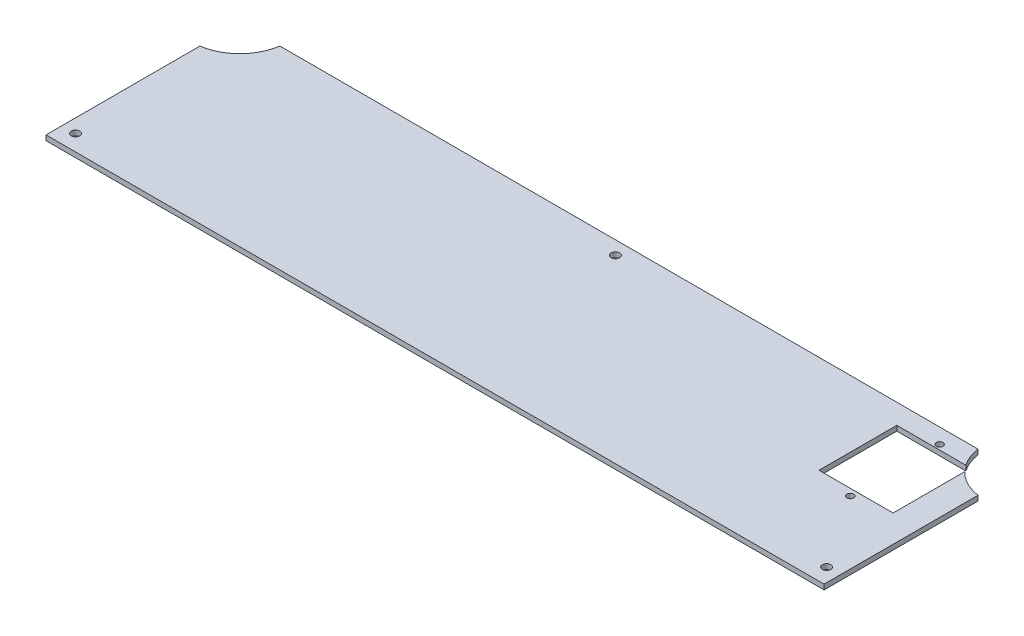
SolidWorks part; units mm, degrees
ref_plane "Alzado" through (0, 0, 0) normal (0, 0, 1) x (1, 0, 0)
ref_plane "Planta" through (0, 0, 0) normal (0, 1, 0) x (1, 0, 0)
ref_plane "Vista lateral" through (0, 0, 0) normal (1, 0, 0) x (0, 0, -1)
sketch "Croquis1" plane through (0, 0, 0) normal (0, 1, 0) x (1, 0, 0)
  line L0 (-230.75, -57.5) -> (230.75, -57.5)
  line L1 (-230.75, 33.7872) -> (-230.75, -57.5)
  line L2 (207.0372, 57.5) -> (-207.0372, 57.5)
  line L3 (170.75, 45.6295) -> (211.6821, 45.6295)
  line L4 (170.75, -0.5) -> (170.75, 45.6295)
  line L5 (214.6745, -0.5) -> (170.75, -0.5)
  line L6 (214.6745, 41.9814) -> (214.6745, -0.5)
  line L7 (230.75, -57.5) -> (230.75, 33.7872)
  arc A5 (-230.75, 33.7872) -> (-207.0372, 57.5) centre (-234.75, 61.5) ccw
  arc A6 (207.0372, 57.5) -> (211.6821, 45.6295) centre (234.75, 61.5) ccw
  arc A7 (214.6745, 41.9814) -> (230.75, 33.7872) centre (234.75, 61.5) ccw
  circle A8 centre (0, 49.5) radius 2.5
  circle A9 centre (193.25, 48.5) radius 2
  circle A10 centre (193.25, -4.5) radius 2
  circle A11 centre (222.75, -48) radius 2.5
  circle A12 centre (-222.75, -48) radius 2.5
  dimension "D1" = 5
  dimension "D2" = 4
  dimension "D3" = 4
  dimension "D4" = 5
  dimension "D5" = 5
extrude "Saliente-Extruir1" add sketch "Croquis1" along normal blind 3
